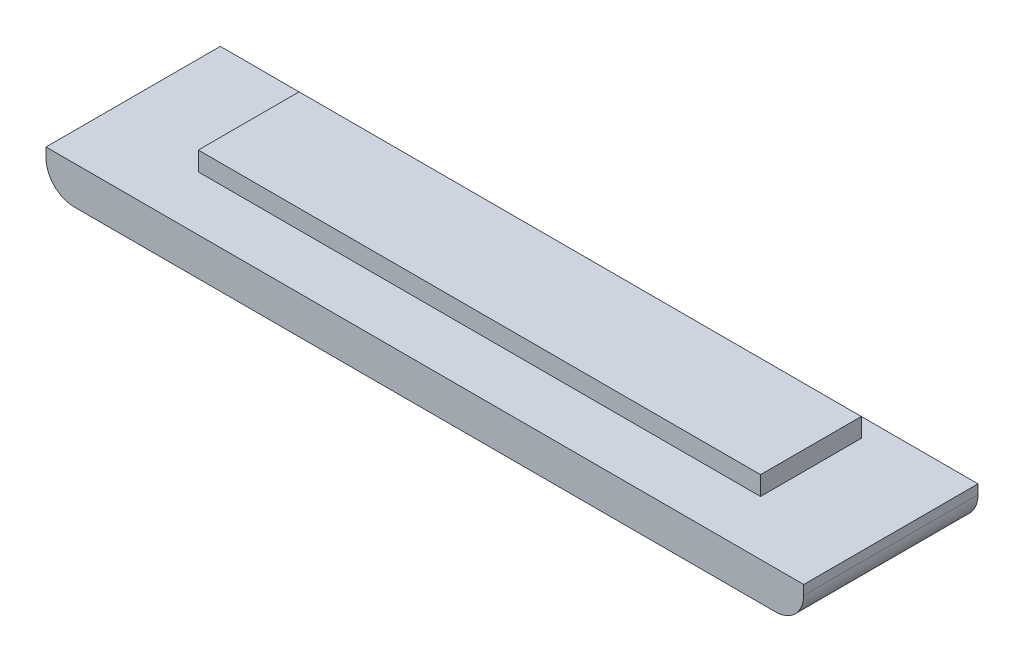
SolidWorks part; units mm, degrees
ref_plane "Front Plane" through (0, 0, 0) normal (0, 0, 1) x (1, 0, 0)
ref_plane "Top Plane" through (0, 0, 0) normal (0, 1, 0) x (1, 0, 0)
ref_plane "Right Plane" through (0, 0, 0) normal (1, 0, 0) x (0, 0, -1)
sketch "Sketch1" plane through (0, 0, 0) normal (0, 1, 0) x (1, 0, 0)
  line L1 (0, 0) -> (254, 0)
  line L2 (0, 0) -> (0, 58.42)
  line L3 (0, 58.42) -> (254, 58.42)
  line L4 (254, 0) -> (254, 58.42)
  dimension "D1" = 254
  dimension "D2" = 58.42
extrude "Boss-Extrude1" add sketch "Sketch1" along normal blind 19.05
sketch "Sketch2" plane through (0, 19.05, 0) normal (0, 1, 0) x (1, 0, 0)
  line L0 (221.234, 18.288) -> (221.234, 52.07)
  line L1 (221.234, 52.07) -> (32.766, 52.07)
  line L2 (221.234, 18.288) -> (32.766, 18.288)
  line L3 (127, 0) -> (127, 58.42) construction
  line L4 (0, 0) -> (254, 0) construction
  line L5 (254, 58.42) -> (0, 58.42) construction
  line L6 (254, 0) -> (254, 58.42) construction
  line L7 (32.766, 18.288) -> (32.766, 52.07)
  point P13 (127, 52.07)
  point P14 (127, 18.288)
  line M5 (0, 58.42) -> (0, 0)
  line M6 (0, 0) -> (254, 0)
  line M7 (254, 0) -> (254, 58.42)
  line M8 (254, 58.42) -> (0, 58.42)
  dimension "D1" = 18.288
  dimension "D2" = 6.35
  dimension "D3" = 32.766
extrude "Cut-Extrude1" cut sketch "Sketch2" against normal blind 6.35 contours L3 L1 L0 L2 M6 M7 M8 | L3 L2 L7 L1 M6 M8 M5
fillet "Fillet1" radius 9.525 2 edges at (254, 0, -29.21) (0, 0, -29.21)
